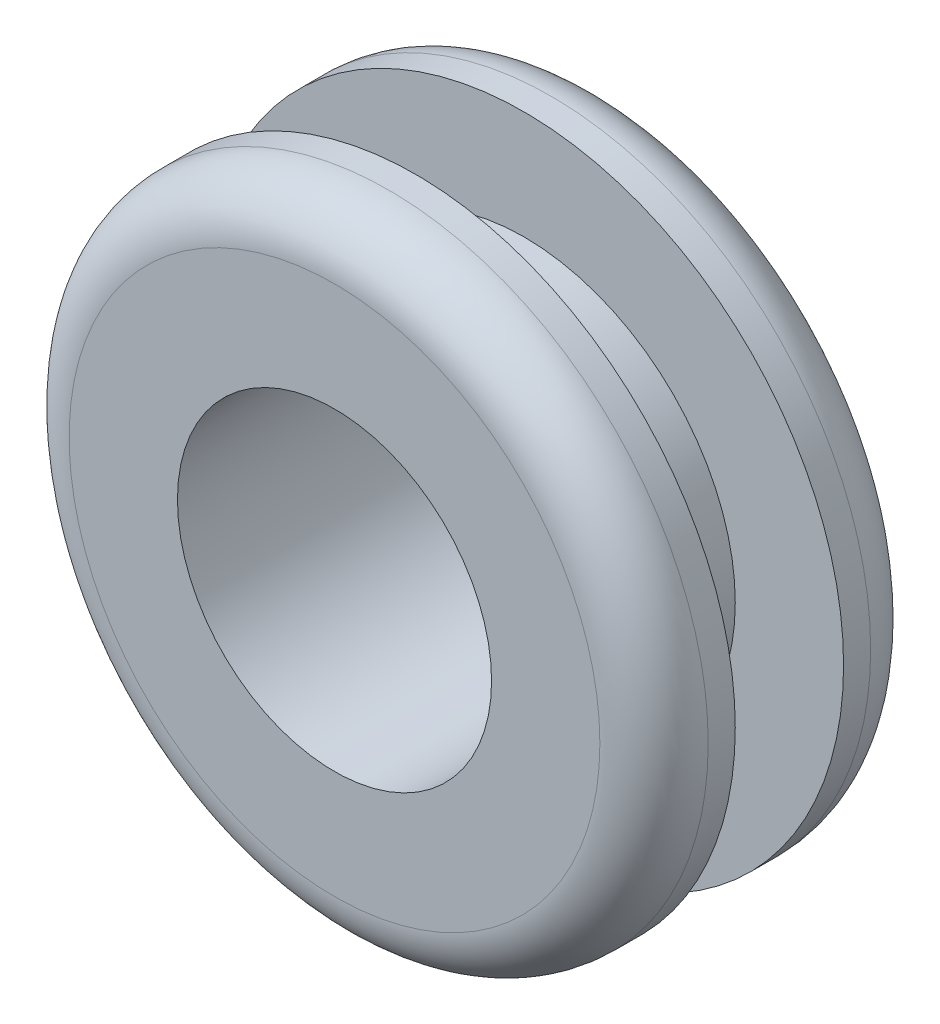
SolidWorks part; units mm, degrees
ref_plane "Ön Düzlem" through (0, 0, 0) normal (0, 0, 1) x (1, 0, 0)
ref_plane "Üst Düzlem" through (0, 0, 0) normal (0, 1, 0) x (1, 0, 0)
ref_plane "Sağ Düzlem" through (0, 0, 0) normal (1, 0, 0) x (0, 0, -1)
sketch "Çizim2" plane through (0, 0, 0) normal (0, 1, 0) x (0, 0, -1)
  line L0 (-2.5, 2.9) -> (2.5, 2.9)
  line L1 (2.5, 2.9) -> (2.5, 4.9)
  line L2 (1.5, 5.9) -> (1, 5.9)
  line L3 (1, 5.9) -> (1, 3.9)
  line L4 (1, 3.9) -> (-1, 3.9)
  line L5 (-1, 3.9) -> (-1, 5.9)
  line L6 (-1, 5.9) -> (-1.5, 5.9)
  line L7 (-2.5, 4.9) -> (-2.5, 2.9)
  arc A0 (-1.5, 5.9) -> (-2.5, 4.9) centre (-1.5, 4.9) ccw
  arc A1 (2.5, 4.9) -> (1.5, 5.9) centre (1.5, 4.9) ccw
  point P6 (0, 2.9)
  point P9 (0, 3.9)
  dimension "D6" = 1
  dimension "D1" = 5
  dimension "D2" = 5.9
  dimension "D3" = 2
  dimension "D4" = 2.9
  dimension "D5" = 2
  dimension "D7" = 2
sketch "Çizim3" plane through (0, 0, 0) normal (0, 1, 0) x (1, 0, 0)
  line L0 (0, 0) -> (0, 1.339) construction
revolve "Döndür2" add sketch "Çizim2" angle 360 about L0
